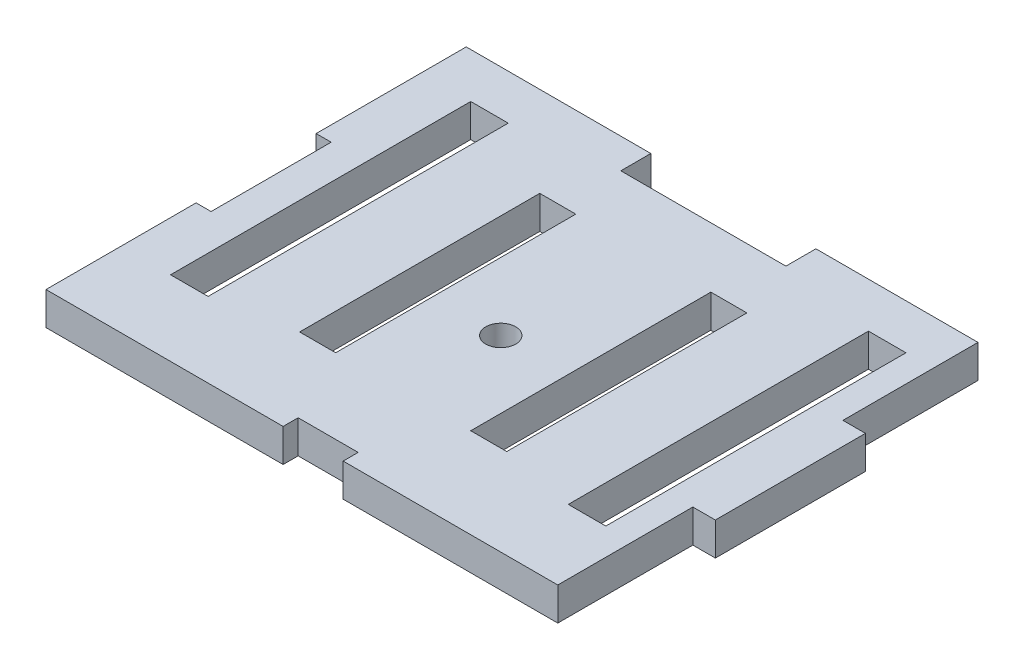
SolidWorks part; units mm, degrees
material "cardboard"
ref_plane "Front Plane" through (0, 0, 0) normal (0, 0, 1) x (1, 0, 0)
ref_plane "Top Plane" through (0, 0, 0) normal (0, 1, 0) x (1, 0, 0)
ref_plane "Right Plane" through (0, 0, 0) normal (1, 0, 0) x (0, 0, -1)
sketch "Sketch1" plane through (0, 0, 0) normal (0, 1, 0) x (1, 0, 0)
  line L0 (-128.8591, 125.026) -> (-117.8591, 125.026)
  line L1 (-118.8591, 121.026) -> (-118.8591, 105.026)
  line L2 (-59.0591, 121.026) -> (-59.0591, 105.026)
  line L3 (-116.4591, 105.026) -> (-118.8591, 105.026)
  line L4 (-130.2591, 121.026) -> (-127.8591, 121.026)
  line L5 (-130.2591, 121.026) -> (-130.2591, 105.026)
  line L6 (-130.2591, 105.026) -> (-127.8591, 105.026)
  line L7 (-127.8591, 121.026) -> (-127.8591, 105.026)
  line L8 (-116.4591, 121.026) -> (-116.4591, 105.026)
  line L9 (-116.4591, 121.026) -> (-118.8591, 121.026)
  line L10 (-56.6591, 121.026) -> (-56.6591, 105.026)
  line L11 (-93.2591, 125.026) -> (-82.2591, 125.026)
  line L12 (-59.0591, 121.026) -> (-56.6591, 121.026)
  line L13 (-59.0591, 105.026) -> (-56.6591, 105.026)
  line L14 (-47.6591, 121.026) -> (-47.6591, 105.026)
  line L15 (-45.2591, 121.026) -> (-47.6591, 121.026)
  line L16 (-45.2591, 121.026) -> (-45.2591, 105.026)
  line L17 (-45.2591, 105.026) -> (-47.6591, 105.026)
  line L18 (12.1409, 121.026) -> (12.1409, 105.026)
  line L19 (14.5409, 121.026) -> (14.5409, 105.026)
  line L20 (12.1409, 121.026) -> (14.5409, 121.026)
  line L21 (12.1409, 105.026) -> (14.5409, 105.026)
  line L22 (23.5409, 121.026) -> (23.5409, 105.026)
  line L23 (25.9409, 121.026) -> (23.5409, 121.026)
  line L24 (25.9409, 121.026) -> (25.9409, 105.026)
  line L25 (25.9409, 105.026) -> (23.5409, 105.026)
  line L26 (83.3409, 121.026) -> (83.3409, 105.026)
  line L27 (85.7409, 121.026) -> (85.7409, 105.026)
  line L28 (-57.6591, 125.026) -> (-46.6591, 125.026)
  line L30 (83.3409, 121.026) -> (85.7409, 121.026)
  line L31 (83.3409, 105.026) -> (85.7409, 105.026)
  line L32 (94.7409, 121.026) -> (94.7409, 105.026)
  line L34 (60.1409, 127.026) -> (84.7409, 127.026)
  line L35 (97.1409, 121.026) -> (94.7409, 121.026)
  line L36 (97.1409, 121.026) -> (97.1409, 105.026)
  line L37 (97.1409, 105.026) -> (94.7409, 105.026)
  line L38 (66.198, 34.9894) -> (72.6139, 28.5735)
  line L39 (86.1008, 15.0866) -> (88.0807, 17.0665)
  line L40 (66.198, 34.9894) -> (68.1779, 36.9693)
  line L41 (79.685, 21.5024) -> (86.1008, 15.0866)
  line L42 (86.1008, -87.7644) -> (79.685, -94.1802)
  line L43 (86.1008, -87.7644) -> (88.0807, -89.7443)
  line L44 (88.0807, -89.7443) -> (68.1779, -109.647)
  line L45 (66.198, -107.6671) -> (68.1779, -109.647)
  line L46 (72.6139, -101.2513) -> (66.198, -107.6671)
  line L47 (-36.6529, -107.6671) -> (-43.0688, -101.2513)
  line L48 (-36.6529, -107.6671) -> (-38.6328, -109.647)
  line L49 (-38.6328, -109.647) -> (-58.5356, -89.7443)
  line L50 (-56.5557, -87.7644) -> (-58.5356, -89.7443)
  line L51 (-50.1399, -94.1802) -> (-56.5557, -87.7644)
  line L52 (-22.0591, 125.026) -> (-11.0591, 125.026)
  line L53 (13.5409, 125.026) -> (24.5409, 125.026)
  line L54 (49.1409, 125.026) -> (60.1409, 125.026)
  line L55 (84.7409, 125.026) -> (95.7409, 125.026)
  line L56 (120.3409, 125.026) -> (131.3409, 125.026)
  line L57 (-33.3295, -104.3437) -> (-31.2601, -106.4132)
  line L58 (-2.9239, -78.1808) -> (-0.8545, -80.2502)
  line L59 (-53.2323, -84.441) -> (-55.0001, -86.2087)
  line L60 (-33.3295, -104.3437) -> (-35.0973, -106.1115)
  line L65 (-29.1388, -51.9659) -> (-55.3017, -78.1289)
  line L66 (-55.3017, -82.3715) -> (-53.2323, -84.441)
  line L67 (-0.8545, -80.2502) -> (-27.0175, -106.4132)
  line L68 (-29.1388, -51.9659) -> (-27.0694, -54.0354)
  line L72 (-141.1591, 127.026) -> (-128.8591, 127.026)
  line L84 (-52.5434, 79.7277) -> (-52.5434, 84.7277)
  line L85 (-62.5434, 79.7277) -> (-62.5434, 84.7277)
  line L86 (-31.9935, 71.2156) -> (-28.4579, 74.7511)
  line L87 (-24.9224, 64.1445) -> (-21.3869, 67.6801)
  line L88 (-16.4103, 43.5946) -> (-11.4103, 43.5946)
  line L89 (-16.4103, 33.5946) -> (-11.4103, 33.5946)
  line L90 (-24.9224, 13.0447) -> (-21.3869, 9.5092)
  line L91 (-31.9935, 5.9737) -> (-28.4579, 2.4381)
  line L92 (-52.5434, -2.5384) -> (-52.5434, -7.5384)
  line L93 (-62.5434, -2.5384) -> (-62.5434, -7.5384)
  line L94 (-83.0933, 5.9737) -> (-86.6288, 2.4381)
  line L108 (64.6424, 33.4337) -> (71.0583, 27.0179)
  line L109 (78.1293, 19.9468) -> (84.5452, 13.531)
  line L110 (78.1293, 19.9468) -> (79.685, 21.5024)
  line L111 (71.0583, 27.0179) -> (72.6139, 28.5735)
  line L112 (32.8459, -79.9719) -> (35.6744, -77.1435)
  line L113 (58.4056, -18.2655) -> (55.5772, -15.4371)
  line L114 (-141.1591, 127.026) -> (-141.1591, 117.026)
  line L115 (-3.3008, 7.2941) -> (-28.8605, -18.2655)
  line L116 (-141.1591, 99.026) -> (-125.3591, 99.026)
  line L117 (-90.1643, 13.0447) -> (-93.6999, 9.5092)
  line L118 (-105.5591, 118.026) -> (-105.5591, 108.026)
  line L119 (68.1779, 36.9693) -> (88.0807, 17.0665)
  line L120 (-19.6447, -50.8534) -> (0.258, -70.7562)
  line L121 (-19.6447, -50.8534) -> (-22.8267, -54.0354)
  line L122 (0.258, -70.7562) -> (-2.9239, -73.9382)
  line L123 (-28.8605, -18.2655) -> (-63.8605, -18.2655)
  line L124 (-78.8605, -33.2655) -> (-78.8605, -39.4123)
  line L125 (-63.8605, -54.4123) -> (-31.5851, -54.4123)
  line L126 (-108.8591, 104.026) -> (-111.3591, 104.026)
  line L127 (-137.8591, 124.026) -> (-135.3591, 124.026)
  line L128 (-137.8591, 124.026) -> (-137.8591, 104.026)
  line L129 (-137.8591, 104.026) -> (-135.3591, 104.026)
  line L130 (-135.3591, 124.026) -> (-135.3591, 104.026)
  line L131 (-111.3591, 124.026) -> (-111.3591, 104.026)
  line L132 (32.8459, 7.2941) -> (32.8459, 42.2941)
  line L133 (17.8459, 57.2941) -> (11.6992, 57.2941)
  line L134 (-3.3008, 42.2941) -> (-3.3008, 7.2941)
  line L135 (-108.8591, 124.026) -> (-111.3591, 124.026)
  line L136 (-108.8591, 124.026) -> (-108.8591, 104.026)
  line L138 (-121.3591, 99.026) -> (-107.0591, 99.026)
  line L140 (-105.5591, 118.026) -> (-105.5591, 108.026)
  line L141 (58.4056, -54.4123) -> (93.4056, -54.4123)
  line L142 (108.4056, -39.4123) -> (108.4056, -33.2655)
  line L143 (93.4056, -18.2655) -> (58.4056, -18.2655)
  line L144 (-71.4591, 99.026) -> (-69.9591, 99.026)
  line L145 (-69.9591, 127.026) -> (-69.9591, 99.026)
  line L146 (24.5409, 127.026) -> (49.1409, 127.026)
  line L147 (-69.9591, 127.026) -> (-69.9591, 99.026)
  line L148 (-69.9591, 99.026) -> (-34.3591, 99.026)
  line L149 (-34.3591, 127.026) -> (-34.3591, 99.026)
  line L150 (-3.3008, -82.6966) -> (-3.3008, -114.9719)
  line L151 (11.6992, -129.9719) -> (17.8459, -129.9719)
  line L152 (32.8459, -114.9719) -> (32.8459, -79.9719)
  line L153 (-11.0591, 127.026) -> (13.5409, 127.026)
  line L154 (-34.3591, 127.026) -> (-34.3591, 99.026)
  line L155 (-34.3591, 99.026) -> (1.2409, 99.026)
  line L156 (1.2409, 127.026) -> (1.2409, 99.026)
  line L157 (-46.6591, 127.026) -> (-22.0591, 127.026)
  line L158 (1.2409, 127.026) -> (1.2409, 99.026)
  line L159 (55.5772, -57.2407) -> (58.4056, -54.4123)
  line L160 (29.2871, -70.7562) -> (49.1898, -50.8534)
  line L161 (84.5452, -86.2087) -> (78.1293, -92.6246)
  line L162 (49.1898, -50.8534) -> (84.5452, -86.2087)
  line L163 (78.1293, -92.6246) -> (79.685, -94.1802)
  line L164 (81.6649, -96.1601) -> (74.5938, -103.2312)
  line L165 (29.2871, -70.7562) -> (64.6424, -106.1115)
  line L166 (71.0583, -99.6957) -> (72.6139, -101.2513)
  line L167 (71.0583, -99.6957) -> (64.6424, -106.1115)
  line L168 (-35.0973, -106.1115) -> (-41.5131, -99.6957)
  line L169 (-41.5131, -99.6957) -> (-43.0688, -101.2513)
  line L170 (35.6744, 4.4657) -> (32.8459, 7.2941)
  line L171 (-98.6764, 33.5946) -> (-103.6764, 33.5946)
  line L172 (49.1898, -21.8244) -> (29.2871, -1.9216)
  line L173 (49.1898, -21.8244) -> (84.5452, 13.531)
  line L174 (29.2871, -1.9216) -> (64.6424, 33.4337)
  line L175 (-45.0487, -103.2312) -> (-52.1197, -96.1601)
  line L176 (-48.5842, -92.6246) -> (-50.1399, -94.1802)
  line L177 (-48.5842, -92.6246) -> (-55.0001, -86.2087)
  line L178 (-62.5434, 79.7277) -> (-74.5812, 79.7277)
  line L179 (-74.5812, 79.7277) -> (-83.0933, 71.2156)
  line L180 (1.2409, 99.026) -> (36.8409, 99.026)
  line L181 (36.8409, 127.026) -> (36.8409, 99.026)
  line L182 (-82.2591, 127.026) -> (-57.6591, 127.026)
  line L183 (36.8409, 127.026) -> (36.8409, 99.026)
  line L184 (36.8409, 99.026) -> (72.4409, 99.026)
  line L185 (72.4409, 127.026) -> (72.4409, 99.026)
  line L186 (-117.8591, 127.026) -> (-107.0591, 127.026)
  line L187 (72.4409, 127.026) -> (72.4409, 99.026)
  line L188 (72.4409, 99.026) -> (108.0409, 99.026)
  line L189 (108.0409, 127.026) -> (108.0409, 99.026)
  line L190 (131.3409, 127.026) -> (143.6409, 127.026)
  line L191 (108.0409, 127.026) -> (108.0409, 99.026)
  line L192 (108.0409, 99.026) -> (143.6409, 99.026)
  line L193 (143.6409, 127.026) -> (143.6409, 117.026)
  line L194 (-66.6591, 124.026) -> (-64.1591, 124.026)
  line L195 (-66.6591, 124.026) -> (-66.6591, 104.026)
  line L196 (-66.6591, 104.026) -> (-64.1591, 104.026)
  line L197 (-64.1591, 124.026) -> (-64.1591, 104.026)
  line L198 (-40.1591, 124.026) -> (-40.1591, 104.026)
  line L199 (-37.6591, 104.026) -> (-40.1591, 104.026)
  line L200 (-37.6591, 124.026) -> (-37.6591, 104.026)
  line L201 (-37.6591, 124.026) -> (-40.1591, 124.026)
  line L202 (-58.1591, 99.026) -> (-58.1591, 95.026)
  line L203 (-58.1591, 95.026) -> (-46.1591, 95.026)
  line L204 (-46.1591, 95.026) -> (-46.1591, 99.026)
  line L205 (4.5409, 124.026) -> (7.0409, 124.026)
  line L206 (4.5409, 124.026) -> (4.5409, 104.026)
  line L207 (4.5409, 104.026) -> (7.0409, 104.026)
  line L208 (7.0409, 124.026) -> (7.0409, 104.026)
  line L209 (31.0409, 124.026) -> (31.0409, 104.026)
  line L210 (33.5409, 104.026) -> (31.0409, 104.026)
  line L211 (33.5409, 124.026) -> (33.5409, 104.026)
  line L212 (33.5409, 124.026) -> (31.0409, 124.026)
  line L213 (13.0409, 99.026) -> (13.0409, 95.026)
  line L214 (13.0409, 95.026) -> (25.0409, 95.026)
  line L215 (25.0409, 95.026) -> (25.0409, 99.026)
  line L216 (75.7409, 124.026) -> (78.2409, 124.026)
  line L217 (75.7409, 124.026) -> (75.7409, 104.026)
  line L218 (75.7409, 104.026) -> (78.2409, 104.026)
  line L219 (78.2409, 124.026) -> (78.2409, 104.026)
  line L220 (102.2409, 124.026) -> (102.2409, 104.026)
  line L221 (104.7409, 104.026) -> (102.2409, 104.026)
  line L222 (104.7409, 124.026) -> (104.7409, 104.026)
  line L223 (104.7409, 124.026) -> (102.2409, 124.026)
  line L224 (84.2409, 99.026) -> (84.2409, 95.026)
  line L225 (84.2409, 95.026) -> (96.2409, 95.026)
  line L226 (96.2409, 95.026) -> (96.2409, 99.026)
  line L228 (-125.3591, 99.026) -> (-125.3591, 100.026)
  line L229 (-125.3591, 100.026) -> (-121.3591, 100.026)
  line L230 (-121.3591, 100.026) -> (-121.3591, 99.026)
  line L232 (-58.1591, 98.026) -> (-54.1591, 98.026)
  line L233 (-54.1591, 98.026) -> (-54.1591, 100.026)
  line L234 (-54.1591, 100.026) -> (-50.1591, 100.026)
  line L235 (-50.1591, 100.026) -> (-50.1591, 98.026)
  line L236 (-50.1591, 98.026) -> (-46.1591, 98.026)
  line L237 (13.0409, 98.026) -> (17.0409, 98.026)
  line L238 (17.0409, 98.026) -> (17.0409, 100.026)
  line L239 (17.0409, 100.026) -> (21.0409, 100.026)
  line L240 (30.7013, -0.5074) -> (37.0652, -6.8713)
  line L241 (37.0652, -6.8713) -> (34.2368, -9.6998)
  line L242 (34.2368, -9.6998) -> (41.4117, -16.8746)
  line L243 (41.4117, -16.8746) -> (44.2401, -14.0462)
  line L244 (44.2401, -14.0462) -> (50.6041, -20.4102)
  line L245 (50.6041, -52.2676) -> (44.2401, -58.6316)
  line L246 (44.2401, -58.6316) -> (41.4117, -55.8031)
  line L247 (41.4117, -55.8031) -> (34.2368, -62.978)
  line L248 (34.2368, -62.978) -> (37.0652, -65.8064)
  line L249 (37.0652, -65.8064) -> (30.7013, -72.1704)
  line L250 (-1.1562, -72.1704) -> (-7.5201, -65.8064)
  line L251 (-7.5201, -65.8064) -> (-4.6917, -62.978)
  line L252 (-4.6917, -62.978) -> (-11.8666, -55.8031)
  line L253 (-11.8666, -55.8031) -> (-14.695, -58.6316)
  line L254 (-14.695, -58.6316) -> (-21.0589, -52.2676)
  line L255 (-86.6288, 74.7511) -> (-93.6999, 67.6801)
  line L256 (-90.1643, 64.1445) -> (-98.6764, 55.6325)
  line L257 (-98.6764, 55.6325) -> (-98.6764, 43.5946)
  line L258 (-103.6764, 43.5946) -> (-103.6764, 33.5946)
  line L259 (-98.6764, 33.5946) -> (-98.6764, 21.5568)
  line L260 (-98.6764, 21.5568) -> (-90.1643, 13.0447)
  line L261 (-93.6999, 9.5092) -> (-86.6288, 2.4381)
  line L262 (-83.0933, 5.9737) -> (-74.5812, -2.5384)
  line L263 (-74.5812, -2.5384) -> (-62.5434, -2.5384)
  line L264 (-62.5434, -7.5384) -> (-52.5434, -7.5384)
  line L265 (-52.5434, -2.5384) -> (-40.5055, -2.5384)
  line L266 (-40.5055, -2.5384) -> (-31.9935, 5.9737)
  line L267 (-28.4579, 2.4381) -> (-21.3869, 9.5092)
  line L268 (-24.9224, 13.0447) -> (-16.4103, 21.5568)
  line L269 (-16.4103, 21.5568) -> (-16.4103, 33.5946)
  line L270 (-11.4103, 33.5946) -> (-11.4103, 43.5946)
  line L271 (-16.4103, 43.5946) -> (-16.4103, 55.6325)
  line L272 (-16.4103, 55.6325) -> (-24.9224, 64.1445)
  line L273 (-21.3869, 67.6801) -> (-28.4579, 74.7511)
  line L274 (-31.9935, 71.2156) -> (-40.5055, 79.7277)
  line L275 (-40.5055, 79.7277) -> (-52.5434, 79.7277)
  line L276 (-52.5434, 84.7277) -> (-62.5434, 84.7277)
  line L277 (-98.6764, 43.5946) -> (-103.6764, 43.5946)
  line L278 (-90.1643, 64.1445) -> (-93.6999, 67.6801)
  line L279 (-83.0933, 71.2156) -> (-86.6288, 74.7511)
  line L280 (21.0409, 100.026) -> (21.0409, 98.026)
  line L312 (21.0409, 98.026) -> (25.0409, 98.026)
  line L313 (84.2409, 98.026) -> (88.2409, 98.026)
  line L314 (88.2409, 98.026) -> (88.2409, 100.026)
  line L315 (88.2409, 100.026) -> (92.2409, 100.026)
  line L316 (92.2409, 100.026) -> (92.2409, 98.026)
  line L317 (92.2409, 98.026) -> (96.2409, 98.026)
  line L318 (143.6409, 117.026) -> (145.6409, 117.026)
  line L319 (145.6409, 109.026) -> (143.6409, 109.026)
  line L320 (143.6409, 109.026) -> (143.6409, 99.026)
  line L321 (-141.1591, 117.026) -> (-140.1591, 117.026)
  line L322 (-140.1591, 117.026) -> (-140.1591, 109.026)
  line L323 (-140.1591, 109.026) -> (-141.1591, 109.026)
  line L324 (-141.1591, 109.026) -> (-141.1591, 99.026)
  line L325 (-107.0591, 127.026) -> (-107.0591, 118.026)
  line L326 (-107.0591, 118.026) -> (-105.5591, 118.026)
  line L328 (-105.5591, 108.026) -> (-107.0591, 108.026)
  line L329 (-107.0591, 108.026) -> (-107.0591, 99.026)
  line L330 (-71.4591, 127.026) -> (-71.4591, 118.026)
  line L331 (-71.4591, 118.026) -> (-68.4591, 118.026)
  line L332 (-68.4591, 118.026) -> (-68.4591, 108.026)
  line L333 (-68.4591, 108.026) -> (-71.4591, 108.026)
  line L334 (-71.4591, 108.026) -> (-71.4591, 99.026)
  line L335 (-35.8591, 127.026) -> (-35.8591, 118.026)
  line L336 (-35.8591, 118.026) -> (-32.8591, 118.026)
  line L337 (-32.8591, 118.026) -> (-32.8591, 108.026)
  line L338 (-32.8591, 108.026) -> (-35.8591, 108.026)
  line L339 (-35.8591, 108.026) -> (-35.8591, 99.026)
  line L340 (-0.2591, 127.026) -> (-0.2591, 118.026)
  line L341 (-0.2591, 118.026) -> (2.7409, 118.026)
  line L342 (2.7409, 118.026) -> (2.7409, 108.026)
  line L343 (2.7409, 108.026) -> (-0.2591, 108.026)
  line L344 (-0.2591, 108.026) -> (-0.2591, 99.026)
  line L345 (35.3409, 127.026) -> (35.3409, 118.026)
  line L346 (35.3409, 118.026) -> (38.3409, 118.026)
  line L347 (38.3409, 118.026) -> (38.3409, 108.026)
  line L348 (38.3409, 108.026) -> (35.3409, 108.026)
  line L349 (35.3409, 108.026) -> (35.3409, 99.026)
  line L350 (70.9409, 127.026) -> (70.9409, 118.026)
  line L351 (70.9409, 118.026) -> (73.9409, 118.026)
  line L352 (73.9409, 118.026) -> (73.9409, 108.026)
  line L353 (73.9409, 108.026) -> (70.9409, 108.026)
  line L354 (70.9409, 108.026) -> (70.9409, 99.026)
  line L355 (106.5409, 127.026) -> (106.5409, 118.026)
  line L356 (106.5409, 118.026) -> (109.5409, 118.026)
  line L357 (109.5409, 118.026) -> (109.5409, 108.026)
  line L358 (109.5409, 108.026) -> (106.5409, 108.026)
  line L359 (106.5409, 108.026) -> (106.5409, 99.026)
  line L360 (145.6409, 117.026) -> (145.6409, 109.026)
  line L361 (-128.8591, 127.026) -> (-128.8591, 125.026)
  line L362 (-117.8591, 127.026) -> (-117.8591, 125.026)
  line L363 (-93.2591, 127.026) -> (-93.2591, 125.026)
  line L364 (-82.2591, 127.026) -> (-82.2591, 125.026)
  line L365 (-57.6591, 127.026) -> (-57.6591, 125.026)
  line L366 (-46.6591, 127.026) -> (-46.6591, 125.026)
  line L367 (-22.0591, 127.026) -> (-22.0591, 125.026)
  line L368 (-11.0591, 127.026) -> (-11.0591, 125.026)
  line L369 (13.5409, 127.026) -> (13.5409, 125.026)
  line L370 (24.5409, 127.026) -> (24.5409, 125.026)
  line L371 (49.1409, 127.026) -> (49.1409, 125.026)
  line L372 (60.1409, 127.026) -> (60.1409, 125.026)
  line L373 (84.7409, 127.026) -> (84.7409, 125.026)
  line L374 (95.7409, 127.026) -> (95.7409, 125.026)
  line L375 (120.3409, 127.026) -> (120.3409, 125.026)
  line L376 (131.3409, 127.026) -> (131.3409, 125.026)
  line L377 (95.7409, 127.026) -> (120.3409, 127.026)
  circle A0 centre (-29.1388, -59.037) radius 1.75
  circle A1 centre (-57.5434, 65.5946) radius 6
  circle A2 centre (-38.4515, 57.6865) radius 6
  circle A3 centre (-30.5434, 38.5946) radius 6
  circle A4 centre (-7.9256, -80.2502) radius 1.75
  circle A5 centre (-29.1388, -101.4634) radius 1.75
  circle A6 centre (14.7726, 32.2941) radius 10
  circle A7 centre (-123.3591, 111.526) radius 1
  circle A8 centre (-50.352, -80.2502) radius 1.75
  arc A9 (-27.0694, -54.0354) -> (-22.8267, -54.0354) centre (-24.948, -51.914) ccw
  arc A10 (-2.9239, -78.1808) -> (-2.9239, -73.9382) centre (-0.8026, -76.0595) cw
  circle A11 centre (-52.1591, 111.526) radius 1
  circle A12 centre (83.4056, -36.3389) radius 10
  circle A13 centre (14.7726, -36.3389) radius 15
  arc A14 (-63.8605, -18.2655) -> (-78.8605, -33.2655) centre (-63.8605, -33.2655) ccw
  arc A15 (-78.8605, -39.4123) -> (-63.8605, -54.4123) centre (-63.8605, -39.4123) ccw
  arc A16 (-3.3008, -114.9719) -> (11.6992, -129.9719) centre (11.6992, -114.9719) ccw
  arc A17 (17.8459, -129.9719) -> (32.8459, -114.9719) centre (17.8459, -114.9719) ccw
  arc A18 (93.4056, -54.4123) -> (108.4056, -39.4123) centre (93.4056, -39.4123) ccw
  arc A19 (108.4056, -33.2655) -> (93.4056, -18.2655) centre (93.4056, -33.2655) ccw
  arc A20 (32.8459, 42.2941) -> (17.8459, 57.2941) centre (17.8459, 42.2941) ccw
  circle A21 centre (19.0409, 111.526) radius 1
  circle A22 centre (14.7726, -104.9719) radius 10
  circle A23 centre (90.2409, 111.526) radius 1
  circle A24 centre (-53.8605, -36.3389) radius 10
  circle A25 centre (-38.4515, 19.5027) radius 6
  circle A26 centre (-87.7591, 113.026) radius 7.5
  circle A27 centre (-16.5591, 113.026) radius 7.5
  circle A28 centre (54.6409, 113.026) radius 7.5
  circle A29 centre (125.8409, 113.026) radius 7.5
  arc A30 (11.6992, 57.2941) -> (-3.3008, 42.2941) centre (11.6992, 42.2941) ccw
  arc A31 (-31.2601, -106.4132) -> (-27.0175, -106.4132) centre (-29.1388, -104.2918) ccw
  arc A32 (-55.3017, -78.1289) -> (-55.3017, -82.3715) centre (-53.1804, -80.2502) ccw
  circle A33 centre (-57.5434, 11.5946) radius 6
  circle A34 centre (-76.6353, 19.5027) radius 6
  circle A35 centre (-84.5434, 38.5946) radius 6
  circle A36 centre (-76.6353, 57.6865) radius 6
  circle A37 centre (-57.5434, 38.5946) radius 15
  point P72 (14.7726, -36.3389)
  point P118 (14.7726, -36.3389)
  point P209 (14.7726, -36.3389)
  point P211 (14.7726, -36.3389)
  point P221 (14.7726, -36.3389)
  point P227 (14.7726, -36.3389)
  point P291 (14.7726, -36.3389)
  point P313 (14.7726, -36.3389)
  point P324 (14.7726, -36.3389)
  point P358 (-57.5434, 38.5946)
  point P359 (-57.5434, 38.5946)
  point P477 (-57.5434, 38.5946)
extrude "Boss-Extrude1" add sketch "Sketch1" along normal blind 2.2 contours L186 L362 L0 L361 L72 L114 L321 L322 L323 L324 L116 L228 L229 L230 L138 L329 L328 L118 L326 L325 A7 L135 L136 L126 L131 L127 L130 L129 L128 L4 L7 L6 L5 L9 L8 L3 L1
